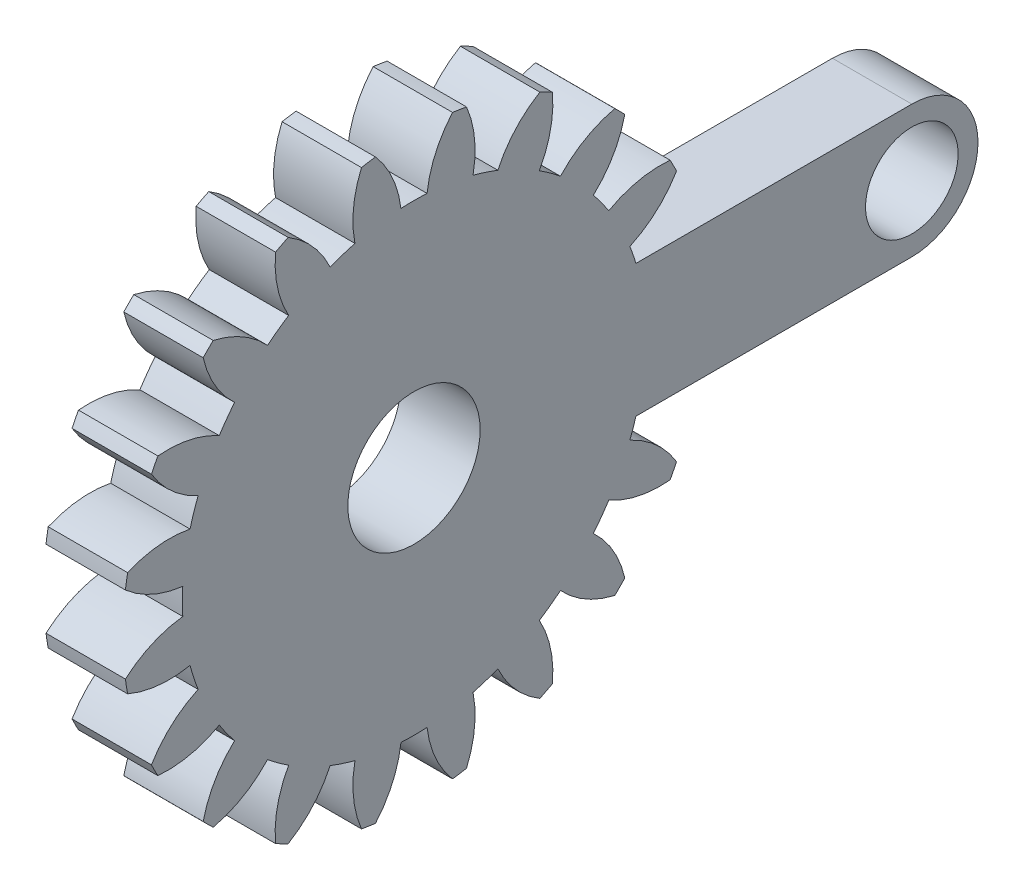
SolidWorks part; units mm, degrees
ref_plane "Plane1" through (0, 0, 0) normal (0, 0, 1) x (1, 0, 0)
ref_plane "Plane2" through (0, 0, 0) normal (0, 1, 0) x (1, 0, 0)
ref_plane "Plane3" through (0, 0, 0) normal (1, 0, 0) x (0, 0, -1)
other "Configuration Table"
sketch "HoldingSke" plane through (0, 0, 0) normal (0, 1, 0) x (1, 0, 0)
  line L0 (0, 0) -> (0.4698, -0.171)
  line L1 (-15, 0) -> (100, 0) construction
  line L2 (0, 0) -> (-2.1039, 2.3779)
  line L3 (0, 0) -> (-11.863, 4.5341)
  line L4 (0, 0) -> (8.1152, 2.9537)
  line L5 (0, 0) -> (-46.8476, -17.4728)
  line L6 (0, 0) -> (-4.9738, -3.3558)
  line L7 (-2.1039, 2.3779) -> (8.6586, 51.2059)
  line L8 (-76.2, 54.61) -> (-75.5, 54.61)
  line L9 (-71.009, 38.7566) -> (-53.1078, 45.2721)
  line L10 (-76.2, 71.12) -> (104.1128, 71.12)
  line L11 (0, 0) -> (-6, 0)
  line L12 (-76.2, 101.6) -> (-76.133, 101.6)
  line L13 (24.9733, 27.94) -> (52.9518, 28.4284)
  line L14 (24.9733, 27.94) -> (24.9743, 27.94)
  line L15 (24.9733, 27.94) -> (100.4006, 29.5858)
  line L16 (-63.627, -2) -> (-12.827, -2)
  circle A0 centre (0, 0) radius 2
  circle A1 centre (0, 0) radius 17.499
  circle A2 centre (0, 0) radius 37.5
  circle A3 centre (0, 0) radius 2
  dimension "MHD" = 34.998
  dimension "Hub_dia" = 75
  dimension "Bore" = 4
  dimension "MBD" = 4
  dimension "Num_teeth" = 20
  dimension "Pitch" = 0.5
  dimension "Overall_len" = 50
  dimension "Show_teeth" = 20
  dimension "Thickness" = 6
  dimension "OAL" = 50.0001
  dimension "T_dim" = 0.7
  dimension "Ap" = 20
  dimension "H" = 19.05
  dimension "Pitch_radius" = 180.3128
  dimension "Width" = 6
  dimension "Backlash" = 0.067
  dimension "Addendum_fac" = 1
  dimension "Dedendum_fac" = 1.25
  dimension "Clearance_fac" = 0.25
  dimension "Dedendum_add" = 0.001
  dimension "Module" = 2
sketch "BasProSke" plane through (0, 0, 0) normal (0, 1, 0) x (1, 0, 0)
  line L0 (-10, 0) -> (60, 0) construction
  line L1 (0, 0) -> (0, 22)
  line L2 (0, 0) -> (6, 0)
  line L3 (6, 0) -> (6, 22)
  line L4 (6, 22) -> (0, 22)
  dimension "Thickness" = 6
  dimension "Diameter" = 44
revolve "Base-Revolve" add sketch "BasProSke" angle 360 about L0
sketch "TooCutSke" plane through (0, 0, 0) normal (1, 0, 0) x (0, 0, -1)
  line L1 (0, 0) -> (0, 107) construction
  line L2 (0, 0) -> (-1.6864, 19.9288) construction
  line L3 (0, 0) -> (-6.2409, 39.4033) construction
  line L4 (-1.6864, 19.9288) -> (-3.1204, 19.7016) construction
  arc A0 (0.9862, 17.4712) -> (-0.9862, 17.4712) centre (0, 0) ccw
  arc A1 (2.9329, 21.8293) -> (-2.9329, 21.8293) centre (0, 0) ccw
  circle A2 centre (0, 0) radius 20 construction
  circle A3 centre (0, 0) radius 18.7939 construction
  arc A4 (-0.9862, 17.4712) -> (-2.9329, 21.8293) centre (-8.9313, 16.536) ccw
  arc A5 (2.9329, 21.8293) -> (0.9862, 17.4712) centre (8.9313, 16.536) ccw
  dimension "Root_dia" = 34.998
  dimension "Overcut_dia" = 44.0508
  dimension "Pitch_dia" = 40
  dimension "Base_dia" = 37.5877
  dimension "Flank_rad" = 8
  dimension "Half_ang" = 9
  dimension "Half_CT" = 1.4519
extrude "ToothCut" cut sketch "TooCutSke" along normal through all
fillet "Breaks" [suppressed] radius 0.04
fillet "RootFillets" [suppressed] radius 0.501
pattern_circular "TeethCuts" count 20 every 18 about axis through (-10, 0, 0) along (1, 0, 0) of "ToothCut", "RootFillets", "Breaks"
sketch "HubNeaOneSke" plane through (0, 0, 0) normal (-1, 0, 0) x (0, 0, 1)
  circle A0 centre (0, 0) radius 17.499
  dimension "Diameter" = 34.998
extrude "HubNearOne" [suppressed] add sketch "HubNeaOneSke" along normal blind 44.0001
sketch "HubNeaBotSke" plane through (0, 0, 0) normal (-1, 0, 0) x (0, 0, 1)
  circle A0 centre (0, 0) radius 17.499
  dimension "Diameter" = 34.998
extrude "HubNearBoth" [suppressed] add sketch "HubNeaBotSke" along normal blind 22
ref_plane "FarPln" through (6, 0, 0) normal (1, 0, 0) x (0, 0, -1)
sketch "HubFarSke" plane through (6, 0, 0) normal (1, 0, 0) x (0, 0, -1)
  circle A0 centre (0, 0) radius 17.499
  dimension "Diameter" = 34.998
extrude "HubFar" [suppressed] add sketch "HubFarSke" along normal blind 22
sketch "BorSke" plane through (0, 0, 0) normal (1, 0, 0) x (0, 0, -1)
  circle A0 centre (0, 0) radius 2
  dimension "Diameter" = 4
extrude "Bore" cut sketch "BorSke" along normal mid plane 100.0001
sketch "KeySke" plane through (0, 0, 0) normal (1, 0, 0) x (0, 0, -1)
  line L0 (-0.8, 0) -> (-0.8, 2.7)
  line L1 (-0.8, 2.7) -> (0.8, 2.7)
  line L2 (0.8, 2.7) -> (0.8, 0)
  line L3 (0, 0) -> (0, 34) construction
  line L4 (-0.8, 0) -> (0.8, 0)
  dimension "Offset" = 2.7
  dimension "Width" = 1.6
extrude "Keyway" [suppressed] cut sketch "KeySke" along normal mid plane 100.0001
pattern_circular "Keyway2" [suppressed] count 2 every 90 about axis through (-10, 0, 0) along (1, 0, 0)
sketch "Sketch1" plane through (6, 0, 0) normal (1, 0, 0) x (0, 0, -1)
  circle A0 centre (0, 0) radius 5
  dimension "D1" = 10
extrude "Cut-Extrude1" cut sketch "Sketch1" against normal through all
sketch "Sketch2" plane through (0, 0, 0) normal (-1, 0, 0) x (0, 0, 1)
  line L0 (0, 5) -> (24.707, 5) construction
  line L1 (-8.9665, -5) -> (-37.6171, -5)
  line L2 (-8.9665, -5) -> (-8.9665, 5)
  line L3 (-8.9665, 5) -> (-37.6171, 5)
  line L4 (-37.6171, -5) -> (-37.6171, 5)
  line L5 (0, -5) -> (25.4692, -5) construction
  circle A0 centre (0, 0) radius 5 construction
  circle A1 centre (-37.6171, 0) radius 5
  dimension "D1" = 10
extrude "Boss-Extrude1" add sketch "Sketch2" against normal up to surface (6 mm away) contours A1 L1 L2 L3 | L4 A1 | L4 A1 up to face at (6, 0, -5)
sketch "Sketch3" plane through (0, 0, 0) normal (-1, 0, 0) x (0, 0, 1)
  circle A0 centre (-37.6171, 0) radius 3.5
  dimension "D1" = 7
extrude "Cut-Extrude2" cut sketch "Sketch3" against normal up to surface (6 mm away) contours A0 up to face at (6, 0, 0.557)
equation "' \"Module@HoldingSke\" = 6.35"
equation "' \"Num_teeth@HoldingSke\" = 12"
equation "' \"Ap@HoldingSke\" =  20"
equation "' \"Ap@HoldingSke\" = 20"
equation "' \"Width@HoldingSke\" = 0.5 * 25.4"
equation "' \"Hub_dia@HoldingSke\"= 1 * 25.4"
equation "' \"Hub_dia@HoldingSke\" = 1 * 25.4"
equation "' \"Overall_len@HoldingSke\" = 1.0 * 25.4"
equation "' \"Bore@HoldingSke\" = 0.75 * 25.4"
equation "' \"T_dim@HoldingSke\" = 0.1 * 25.4"
equation "' \"Width@KeySke\" = 0.25 * 25.4"
equation "' \"Show_teeth@HoldingSke\" = 13"
equation "' \"Backlash@HoldingSke\" = 0.009 * 25.4"
equation "' \"Addendum_fac@HoldingSke\" = 1.0"
equation "' \"Dedendum_fac@HoldingSke\" = 1.25"
equation "' \"Dedendum_add@HoldingSke\" = 0.00005 * 25.4"
equation "' \"Clearance_fac@HoldingSke\" = 0.25"
equation "\"Pitch@HoldingSke\" = 1 / \"Module@HoldingSke\""
equation "\"Overcut_dia@TooCutSke\" = (\"Num_teeth@HoldingSke\" + 2 * \"Addendum_fac@HoldingSke\") / \"Pitch@HoldingSke\" + 0.002 * 25.4"
equation "\"Pitch_dia@TooCutSke\" = \"Num_teeth@HoldingSke\" / \"Pitch@HoldingSke\""
equation "\"Base_dia@TooCutSke\" = \"Num_teeth@HoldingSke\" / \"Pitch@HoldingSke\" * cos((\"Ap@HoldingSke\"  * 3.14159265 / 180))"
equation "\"Root_dia@TooCutSke\" = (\"Num_teeth@HoldingSke\" + 2) / \"Pitch@HoldingSke\" - 2 * (\"Addendum_fac@HoldingSke\" + \"Dedendum_fac@HoldingSke\") / \"Pitch@HoldingSke\" - \"Dedendum_add@HoldingSke\" * 2"
equation "\"Half_ang@TooCutSke\" = 180 / \"Num_teeth@HoldingSke\""
equation "\"Half_CT@TooCutSke\" = \"Num_teeth@HoldingSke\" / \"Pitch@HoldingSke\" * sin((3.14159265 / 2 / \"Num_teeth@HoldingSke\")) / 2 - 7 * \"Backlash@HoldingSke\" / 4"
equation "\"Flank_rad@TooCutSke\" = \"Num_teeth@HoldingSke\" / \"Pitch@HoldingSke\" / 5"
equation "\"Radius@RootFillets\" = \"Clearance_fac@HoldingSke\" / \"Pitch@HoldingSke\" + \"Dedendum_add@HoldingSke\""
equation "\"Break_rad@Breaks\" = 0.02 / \"Pitch@HoldingSke\""
equation "\"Thickness@HoldingSke\" = \"Width@HoldingSke\""
equation "\"OAL@HoldingSke\" = \"Thickness@HoldingSke\""
equation "\"MHD@HoldingSke\" = (\"Num_teeth@HoldingSke\" + 2) / \"Pitch@HoldingSke\" - 2 * (\"Addendum_fac@HoldingSke\" + \"Dedendum_fac@HoldingSke\")  / \"Pitch@HoldingSke\" - \"Dedendum_add@HoldingSke\" * 2"
equation "\"MBD@HoldingSke\" = (\"Num_teeth@HoldingSke\" + 2) / \"Pitch@HoldingSke\" - 2 * (\"Addendum_fac@HoldingSke\" + \"Dedendum_fac@HoldingSke\")  / \"Pitch@HoldingSke\" - \"Dedendum_add@HoldingSke\" * 2 - 0.002 * 25.4"
equation "\"MHD@HoldingSke\" = ((sgn( \"MHD@HoldingSke\" - \"Hub_dia@HoldingSke\" )-1)*( \"MHD@HoldingSke\" - \"Hub_dia@HoldingSke\" ))/-2+ \"Hub_dia@HoldingSke\""
equation "\"MBD@HoldingSke\" = ((sgn( \"MBD@HoldingSke\" - \"Bore@HoldingSke\" )-1)*( \"MBD@HoldingSke\" - \"Bore@HoldingSke\" ))/-2+ \"Bore@HoldingSke\""
equation "\"OAL@HoldingSke\" = ((sgn( \"OAL@HoldingSke\" - \"Overall_len@HoldingSke\" )+1)*( \"OAL@HoldingSke\" - \"Overall_len@HoldingSke\" ))/2 + \"Overall_len@HoldingSke\" + 0.000002 * 25.4"
equation "\"Num_teeth@TeethCuts\" = int( \"Show_teeth@HoldingSke\" ) + 1"
equation "\"Num_teeth@TeethCuts\" = ((sgn( \"Num_teeth@TeethCuts\" - \"Num_teeth@HoldingSke\" )-1)*( \"Num_teeth@TeethCuts\" - \"Num_teeth@HoldingSke\" ))/-2+ \"Num_teeth@HoldingSke\""
equation "\"Num_teeth@TeethCuts\" = ((sgn( \"Num_teeth@TeethCuts\" - 2.0)+1)*( \"Num_teeth@TeethCuts\" - 2.0))/2 +2.0"
equation "\"Angle@TeethCuts\" = 360.0 / \"Num_teeth@HoldingSke\""
equation "\"Diameter@BasProSke\" = (\"Num_teeth@HoldingSke\" + 2 * \"Addendum_fac@HoldingSke\") / \"Pitch@HoldingSke\""
equation "\"Thickness@BasProSke\"  = \"Thickness@HoldingSke\""
equation "' \"Fillet_rad@BasProSke\" =  \"Thickness@HoldingSke\" * 0.05"
equation "' \"Fillet_rad@BasProSke\" = \"Thickness@HoldingSke\" * 0.05"
equation "\"MHD@HoldingSke\" = ((sgn( \"MHD@HoldingSke\" - \"Root_dia@TooCutSke\" )-1)*( \"MHD@HoldingSke\" - \"Root_dia@TooCutSke\" ))/-2+ \"Root_dia@TooCutSke\""
equation "\"Diameter@HubNeaOneSke\" = \"MHD@HoldingSke\""
equation "\"Length@HubNearOne\" = \"OAL@HoldingSke\" - \"Thickness@BasProSke\""
equation "\"Diameter@HubNeaBotSke\" = \"MHD@HoldingSke\""
equation "\"Length@HubNearBoth\" = ( \"OAL@HoldingSke\" - \"Thickness@BasProSke\" ) / 2.0"
equation "\"Thickness@FarPln\" = \"Thickness@BasProSke\""
equation "\"Diameter@HubFarSke\" = \"MHD@HoldingSke\""
equation "\"Length@HubFar\" = ( \"OAL@HoldingSke\" - \"Thickness@BasProSke\" ) / 2.0"
equation "\"Diameter@BorSke\" = \"MBD@HoldingSke\""
equation "\"D1@Bore\" = \"OAL@HoldingSke\" * 2.0"
equation "\"D1@Keyway\" = \"OAL@HoldingSke\" * 2.0"
equation "\"Offset@KeySke\" = \"T_dim@HoldingSke\" + \"MBD@HoldingSke\" / 2.0"
